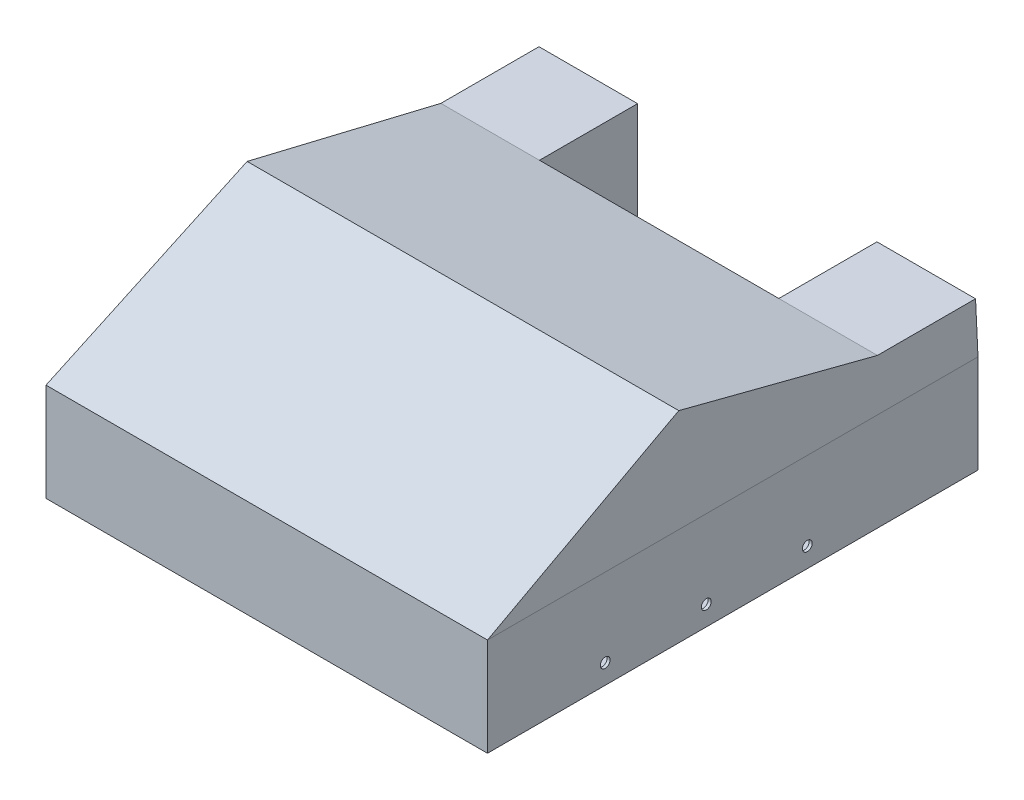
SolidWorks part; units mm, degrees
material "Acrylic (Medium-high impact)"
ref_plane "Front Plane" through (0, 0, 0) normal (0, 0, 1) x (1, 0, 0)
ref_plane "Top Plane" through (0, 0, 0) normal (0, 1, 0) x (1, 0, 0)
ref_plane "Right Plane" through (0, 0, 0) normal (1, 0, 0) x (0, 0, -1)
sketch "Sketch2" plane through (0, 0, 0) normal (1, 0, 0) x (0, 0, -1)
  line L0 (-250, 0) -> (250, 0)
  line L1 (250, 0) -> (250, 150)
  line L3 (-50, 200) -> (-250, 100)
  line L4 (-250, 100) -> (-250, 0)
  line L5 (-50, 200) -> (150, 150)
  line L6 (150, 150) -> (250, 150)
  dimension "D1" = 500
  dimension "D2" = 100
  dimension "D3" = 200
  dimension "D4" = 150
  dimension "D5" = 200
  dimension "D6" = 100
extrude "Boss-Extrude1" add sketch "Sketch2" against normal blind 450
sketch "Sketch3" plane through (0, 0, 0) normal (1, 0, 0) x (0, 0, -1)
  line L12 (-247, 98.1459) -> (-247, 3)
  line L13 (-247, 3) -> (247, 3)
  line L14 (247, 3) -> (247, 147)
  line L15 (247, 147) -> (149.6307, 147)
  line L16 (149.6307, 147) -> (-49.651, 196.8204)
  line L17 (-49.651, 196.8204) -> (-247, 98.1459)
  line L18 (-247, 98.1459) -> (-247, 3)
  line L19 (-247, 3) -> (247, 3)
  line L20 (247, 3) -> (247, 147)
  line L21 (247, 147) -> (149.6307, 147)
  line L22 (149.6307, 147) -> (-49.651, 196.8204)
  line L23 (-49.651, 196.8204) -> (-247, 98.1459)
  dimension "D1" = 3
extrude "Cut-Extrude1" cut sketch "Sketch3" against normal blind 444 from offset 3 offset against normal yes
sketch "Sketch4" plane through (0, 0, -250) normal (0, 0, -1) x (-1, 0, 0)
  line L1 (100, 6) -> (100, 150)
  line L2 (350, 6) -> (350, 150)
  line L3 (100, 150) -> (350, 150)
  line L5 (450, 150) -> (0, 150) construction
  line L6 (0, 0) -> (0, 150) construction
  line L7 (450, 0) -> (450, 150) construction
  line L9 (100, 6) -> (350, 6)
  line L10 (450, 0) -> (0, 0) construction
  dimension "D1" = 100
  dimension "D2" = 100
  dimension "D3" = 6
extrude "Cut-Extrude2" cut sketch "Sketch4" against normal blind 100
sketch "Sketch5" plane through (0, 0, 0) normal (0, -1, 0) x (1, 0, 0)
  circle A0 centre (-225, 0) radius 112.5
  dimension "D1" = 225
extrude "Cut-Extrude3" cut sketch "Sketch5" against normal blind 3
sketch "Sketch7" plane through (0, 0, 0) normal (1, 0, 0) x (0, 0, -1)
  line L0 (-250, 100) -> (-250, 0) construction
  line L1 (-250, 0) -> (250, 0) construction
  circle A0 centre (-130, 20) radius 5
  circle A1 centre (-27, 20) radius 5
  circle A2 centre (76, 20) radius 5
  point P6 (0, 0)
  point P7 (0, 0)
  dimension "D4" = 10
  dimension "D1" = 103
  dimension "D2" = 103
  dimension "D3" = 120
  dimension "D5" = 20
  dimension "D6" = 20
extrude "Cut-Extrude5" cut sketch "Sketch7" against normal through all both and the other way through all
sketch "Sketch9" plane through (0, 0, 0) normal (1, 0, 0) x (0, 0, -1)
  line L0 (-250, 100) -> (250, 100)
  line L1 (250, 0) -> (250, 150) construction
  line L2 (250, 100) -> (250, 150)
  line L3 (250, 150) -> (150, 150)
  line L4 (150, 150) -> (-50, 200)
  line L5 (-50, 200) -> (-250, 100)
extrude "Boss-Extrude2" add sketch "Sketch9" against normal blind 7
sketch "Sketch10" plane through (-450, 0, 0) normal (-1, 0, 0) x (0, 0, 1)
  line L0 (250, 100) -> (50, 200)
  line L1 (50, 200) -> (-150, 150)
  line L2 (-150, 150) -> (-250, 150)
  line L3 (-250, 150) -> (-250, 100)
  line L4 (-250, 0) -> (-250, 150) construction
  line L5 (-250, 100) -> (250, 100)
extrude "Boss-Extrude3" add sketch "Sketch10" against normal blind 7
sketch "Sketch11" plane through (0, 0, 250) normal (0, 0, 1) x (1, 0, 0)
  line L0 (0, 100) -> (0, 200)
  line L1 (0, 200) -> (-5, 200)
  line L2 (-450, 200) -> (0, 200) construction
  line L3 (-5, 200) -> (0, 100)
  line L4 (-450, 200) -> (-450, 100)
  line L5 (-450, 100) -> (-445, 200)
  line L6 (-445, 200) -> (-450, 200)
  dimension "D1" = 5
  dimension "D2" = 5
extrude "Cut-Extrude7" cut sketch "Sketch11" against normal through all both and the other way through all
sketch "Sketch12" plane through (-100, 0, 0) normal (-1, 0, 0) x (0, 0, 1)
  line L1 (-250, 150) -> (-150, 150)
  line L2 (-250, 150) -> (-250, 2.945)
  line L3 (-250, 2.945) -> (-150, 2.945)
  line L4 (-150, 150) -> (-150, 2.945)
  line L5 (-150, 150) -> (-150, 147) construction
  line L6 (-150, 150) -> (-250, 150) construction
  point P5 (-150, 2.945)
  point P7 (-150, 150)
extrude "Boss-Extrude4" add sketch "Sketch12" along normal blind 3
sketch "Sketch14" plane through (-350, 0, 0) normal (1, 0, 0) x (0, 0, -1)
  line L0 (-247, 3) -> (247, 3) construction
  line L1 (250, 150) -> (150, 150)
  line L2 (250, 150) -> (250, 3)
  line L3 (250, 3) -> (150, 3)
  line L4 (150, 150) -> (150, 3)
  point P7 (150, 150)
extrude "Boss-Extrude5" add sketch "Sketch14" along normal blind 3
sketch "Sketch15" plane through (0, 3, 0) normal (0, 1, 0) x (1, 0, 0)
  line L0 (-483.5795, 76) -> (62.6539, 76) construction
  line L1 (-485.808, -27) -> (60.4255, -27) construction
  line L2 (-485.808, -130) -> (60.4255, -130) construction
  line L4 (-450, -250) -> (-450, 250) construction
  line L5 (-225, 340.2694) -> (-225, -345.8647) construction
  line L6 (0, -250) -> (0, 250) construction
  circle A0 centre (-400, 96) radius 2
  circle A1 centre (-400, 56) radius 2
  circle A2 centre (-400, -7) radius 2
  circle A3 centre (-400, -47) radius 2
  circle A4 centre (-400, -110) radius 2
  circle A5 centre (-400, -150) radius 2
  circle A6 centre (-50, -150) radius 2
  circle A7 centre (-50, -110) radius 2
  circle A8 centre (-50, -47) radius 2
  circle A9 centre (-50, -7) radius 2
  circle A10 centre (-50, 56) radius 2
  circle A11 centre (-50, 96) radius 2
  dimension "D1" = 4
  dimension "D2" = 4
  dimension "D7" = 4
  dimension "D3" = 20
  dimension "D4" = 20
  dimension "D5" = 50
  dimension "D6" = 50
  dimension "D8" = 20
  dimension "D9" = 20
  dimension "D10" = 20
  dimension "D11" = 20
  dimension "D12" = 50
extrude "Cut-Extrude8" cut sketch "Sketch15" against normal blind 3
